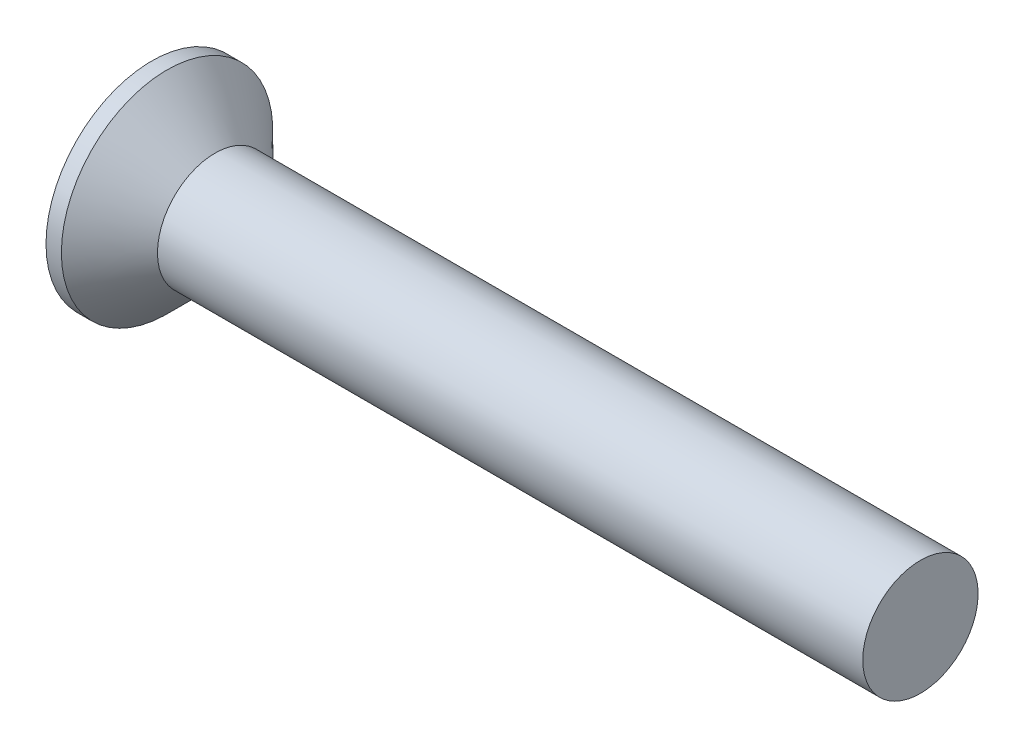
SolidWorks part; units mm, degrees
ref_plane "Plan de face" through (0, 0, 0) normal (0, 0, 1) x (1, 0, 0)
ref_plane "Plan de dessus" through (0, 0, 0) normal (0, 1, 0) x (1, 0, 0)
ref_plane "Plan de droite" through (0, 0, 0) normal (1, 0, 0) x (0, 0, -1)
sketch "Esquisse1" plane through (0, 0, 0) normal (0, 0, 1) x (1, 0, 0)
  line L0 (0, 0) -> (20, 0)
  line L1 (20, 0) -> (20, 1.5)
  line L2 (20, 1.5) -> (1.65, 1.5)
  line L4 (0, 2.75) -> (0, 0)
  line L5 (0, 2.75) -> (0.4, 2.75)
  line L6 (0.4, 2.75) -> (1.65, 1.5)
  dimension "D1" = 20
  dimension "D2" = 1.5
  dimension "D3" = 2.75
  dimension "D4" = 1.65
  dimension "D5" = 45
revolve "Révolution1" add sketch "Esquisse1" angle 360 about L0
equation "\"D3@Esquisse1\"=5.5/2"
